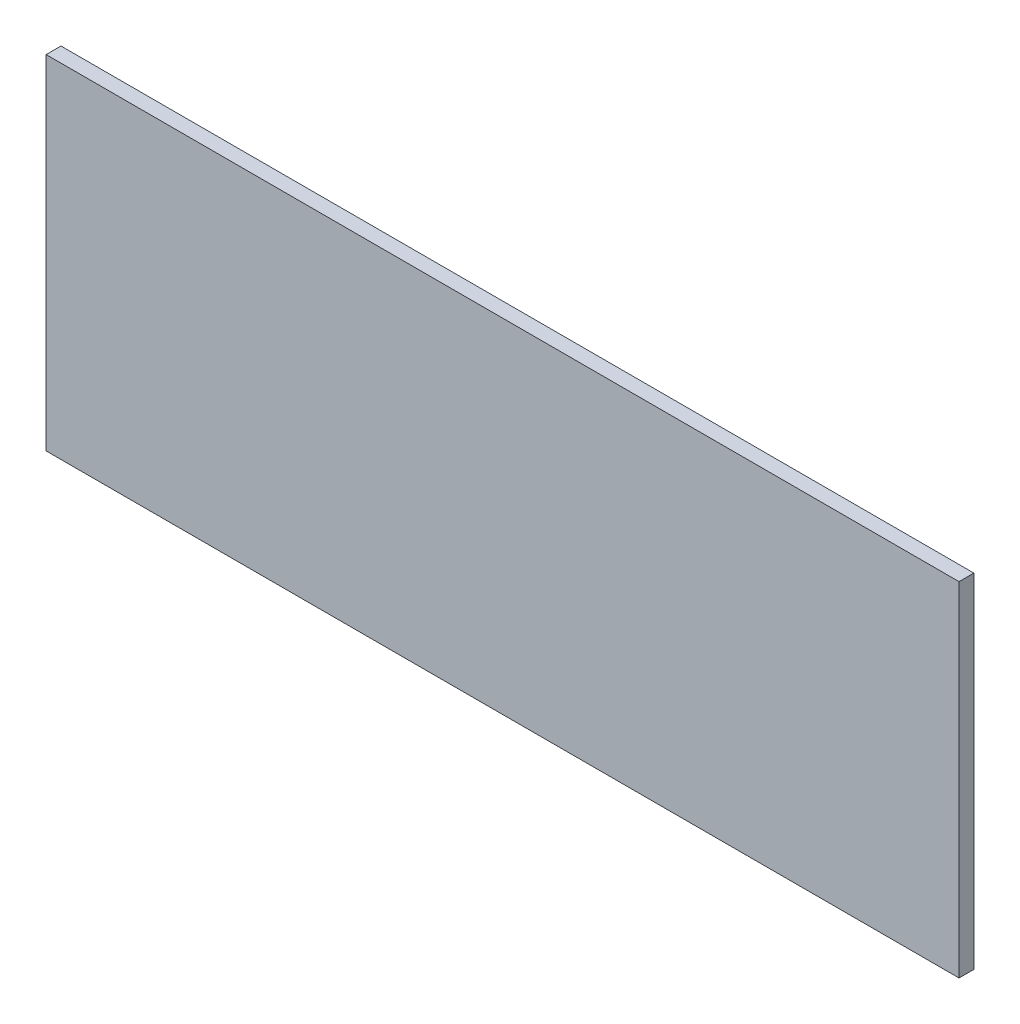
SolidWorks part; units mm, degrees
ref_plane "Plan de face" through (0, 0, 0) normal (0, 0, 1) x (1, 0, 0)
ref_plane "Plan de dessus" through (0, 0, 0) normal (0, 1, 0) x (1, 0, 0)
ref_plane "Plan de droite" through (0, 0, 0) normal (1, 0, 0) x (0, 0, -1)
sketch "Esquisse1" plane through (0, 0, 0) normal (0, 0, 1) x (1, 0, 0)
  line L1 (-70.1076, 160.6759) -> (421.8924, 160.6759)
  line L2 (-70.1076, 160.6759) -> (-70.1076, -24.3241)
  line L3 (-70.1076, -24.3241) -> (421.8924, -24.3241)
  line L4 (421.8924, 160.6759) -> (421.8924, -24.3241)
  dimension "D1" = 492
  dimension "D2" = 185
extrude "Boss.-Extru.1" add sketch "Esquisse1" along normal blind 8
